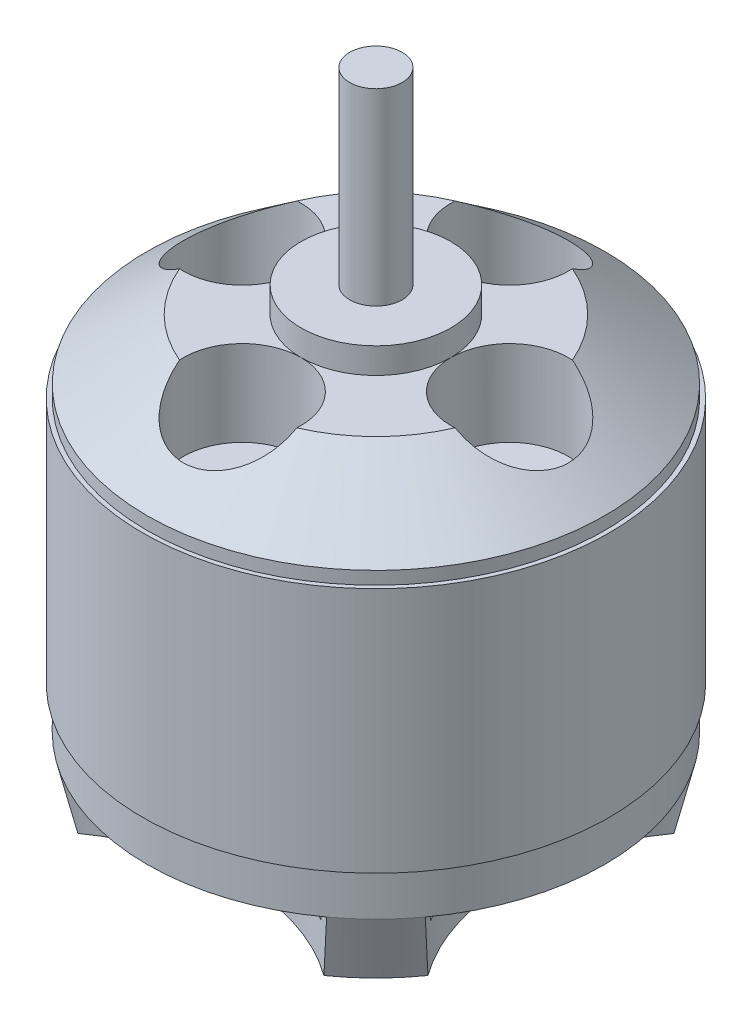
SolidWorks part; units mm, degrees
material "Plain Carbon Steel"
ref_plane "Front" through (0, 0, 0) normal (0, 0, 1) x (1, 0, 0)
ref_plane "Top" through (0, 0, 0) normal (0, 1, 0) x (1, 0, 0)
ref_plane "Right" through (0, 0, 0) normal (1, 0, 0) x (0, 0, -1)
sketch "Sketch1" plane through (0, 0, 0) normal (0, 0, 1) x (1, 0, 0)
  line L0 (0, 11.176) -> (1.5558, 11.176)
  line L1 (0, -50) -> (0, 50) construction
  line L2 (1.5558, 11.176) -> (1.5558, 0)
  line L3 (50, 0) -> (-50, 0) construction
  line L4 (1.5558, 0) -> (4.445, 0)
  line L5 (4.445, 0) -> (4.445, -1.524)
  line L6 (4.445, -1.524) -> (8.89, -1.524)
  line L7 (8.89, -1.524) -> (13.589, -5.08)
  line L8 (13.589, -5.08) -> (13.589, -5.842)
  line L9 (13.589, -5.842) -> (13.843, -5.842)
  line L10 (13.843, -5.842) -> (13.843, -20.4724)
  line L11 (13.589, -20.4724) -> (13.589, -23.0124)
  line L12 (13.589, -23.0124) -> (12.7, -26.67)
  line L13 (12.7, -26.67) -> (3.81, -26.67)
  line L14 (3.81, -26.67) -> (3.81, -26.924)
  line L15 (3.81, -26.924) -> (1.5558, -26.924)
  line L16 (1.5558, -26.924) -> (1.5558, -28.956)
  line L17 (1.5558, -28.956) -> (0, -28.956)
  line L18 (0, -28.956) -> (0, 11.176)
  line L19 (13.589, -20.4724) -> (13.843, -20.4724)
  dimension "D1" = 13.843
  dimension "D2" = 1.5557
  dimension "D3" = 11.176
  dimension "D4" = 4.445
  dimension "D5" = 1.524
  dimension "D6" = 8.89
  dimension "D7" = 4.318
  dimension "D8" = 0.762
  dimension "D9" = 0.254
  dimension "D10" = 14.6304
  dimension "D11" = 2.54
  dimension "D12" = 25.146
  dimension "D13" = 12.7
  dimension "D14" = 3.81
  dimension "D15" = 0.254
  dimension "D16" = 40.132
revolve "Revolve1" add sketch "Sketch1" angle 360 about L18
sketch "Sketch2" plane through (0, -1.524, 0) normal (0, 1, 0) x (1, 0, 0)
  circle A0 centre (0, 7.9375) radius 3.4925
  circle A1 centre (7.9375, 0) radius 3.4925
  circle A2 centre (0, -7.9375) radius 3.4925
  circle A3 centre (-7.9375, 0) radius 3.4925
  circle A5 centre (0, 0) radius 4.445 construction
  circle A7 centre (0, 0) radius 4.445 construction
  dimension "D2" = 6.985
extrude "Cut-Extrude1" cut sketch "Sketch2" against normal blind 5.08
sketch "Sketch3" plane through (0, -26.67, 0) normal (0, -1, 0) x (1, 0, 0)
  line L1 (-7.3025, 10.3905) -> (7.3025, 10.3905) construction
  circle A0 centre (0, 20.4866) radius 12.4602
  circle A1 centre (-20.4866, 0) radius 12.4602
  circle A2 centre (0, -20.4866) radius 12.4602
  circle A3 centre (20.4866, 0) radius 12.4602
  circle A4 centre (0, 0) radius 8.0264 construction
  circle A5 centre (0, 0) radius 12.7 construction
  dimension "D1" = 16.0528
  dimension "D2" = 14.605
extrude "Cut-Extrude2" cut sketch "Sketch3" against normal offset from surface (3.6576 mm away) 2.54 up to face at (0, -20.4724, -13.843)
sketch "Sketch4" plane through (0, -23.0124, 0) normal (0, -1, 0) x (1, 0, 0)
  circle A0 centre (0, 0) radius 12.1158
  arc A2 (8.0324, 10.9609) -> (-8.0324, 10.9609) centre (0, 0) ccw construction
  dimension "D1" = 1.4732
extrude "Cut-Extrude3" cut sketch "Sketch4" against normal blind 2.54 and the other way blind 1.27
hole_wizard "#4-40 Tapped Hole1" positions "Sketch7" profile "Sketch6" tap size "#4-40" standard "ANSI Inch"
sketch "Sketch7" plane through (0, -26.67, 0) normal (0, -1, 0) x (-1, 0, 0)
  line L0 (6.6723, 6.6723) -> (-6.6723, -6.6723) construction
  line L2 (5.6665, -5.6665) -> (-5.6665, 5.6665) construction
  line L5 (0, 0) -> (0, -19.5936) construction
  point P16 (5.6665, -5.6665)
  point P18 (-6.6723, -6.6723)
  point P20 (-5.6665, 5.6665)
  point P22 (6.6723, 6.6723)
  dimension "D1" = 18.8722
  dimension "D2" = 16.0274
  dimension "D3" = 45
sketch "Sketch6" plane through (-5.6665, -26.67, 5.6665) normal (1, 0, 0) x (0, 0, -1)
  line L0 (0, 0) -> (0, 3.2192)
  line L1 (0, 3.2192) -> (1.1303, 2.54)
  line L2 (1.1303, 2.54) -> (1.1303, 0.3937)
  line L3 (1.1303, 0.3937) -> (1.524, 0)
  line L5 (1.524, 0) -> (0, 0)
  line L6 (-1.1303, 0.3937) -> (-1.524, 0) construction
  line L10 (0, 3.2192) -> (-1.1303, 2.54) construction
  line L11 (0, -6.35) -> (0, 107.95) construction
  dimension "Tap Drill Dia." = 2.2606
  dimension "Tap Drill Depth" = 2.54
  dimension "Near C'Sink Dia." = 3.048
  dimension "Near C'Sink Angle" = 90
  dimension "Drill Angle" = 118
cosmetic thread "Hole Thread7" parameters "D1"=2.0853, "D2"=2.8448
cosmetic thread "Hole Thread8" parameters "D1"=2.0853, "D2"=2.8448
cosmetic thread "Hole Thread9" parameters "D1"=2.0853, "D2"=2.8448
cosmetic thread "Hole Thread10" parameters "D1"=2.0853, "D2"=2.8448
sketch "Sketch10" plane through (0, 0, 0) normal (1, 0, 0) x (0, 0, -1)
  line L1 (-12.1158, -20.4724) -> (12.1158, -20.4724) construction
  line L2 (-1.7272, -21.2979) -> (0, -21.2979) construction
  line L3 (0, -21.2979) -> (1.7272, -21.2979) construction
  circle A0 centre (0, -21.2979) radius 0.8255
  circle A1 centre (-1.7272, -21.2979) radius 0.8255
  circle A2 centre (1.7272, -21.2979) radius 0.8255
  dimension "D1" = 1.651
  dimension "D2" = 1.7272
sketch "Sketch12" plane through (0, 0, 0) normal (0, 0, 1) x (1, 0, 0)
  line L0 (0, -21.2979) -> (3.81, -21.2979)
  line L1 (0, -22.1234) -> (0, -20.4724) construction
  line L2 (9.5697, -23.8815) -> (51.689, -23.8815)
  line L3 (-13.843, -20.4724) -> (13.843, -20.4724) construction
  line L4 (-13.843, -20.4724) -> (13.589, -20.4724) construction
  line L5 (13.589, -23.0124) -> (13.589, -20.4724) construction
  arc A0 (3.81, -21.2979) -> (6.6898, -22.5897) centre (3.81, -25.1539) cw
  arc A1 (6.6898, -22.5897) -> (9.5697, -23.8815) centre (9.5697, -20.0255) ccw
  dimension "D1" = 2.5836
  dimension "D2" = 38.1
  dimension "D3" = 3.81
